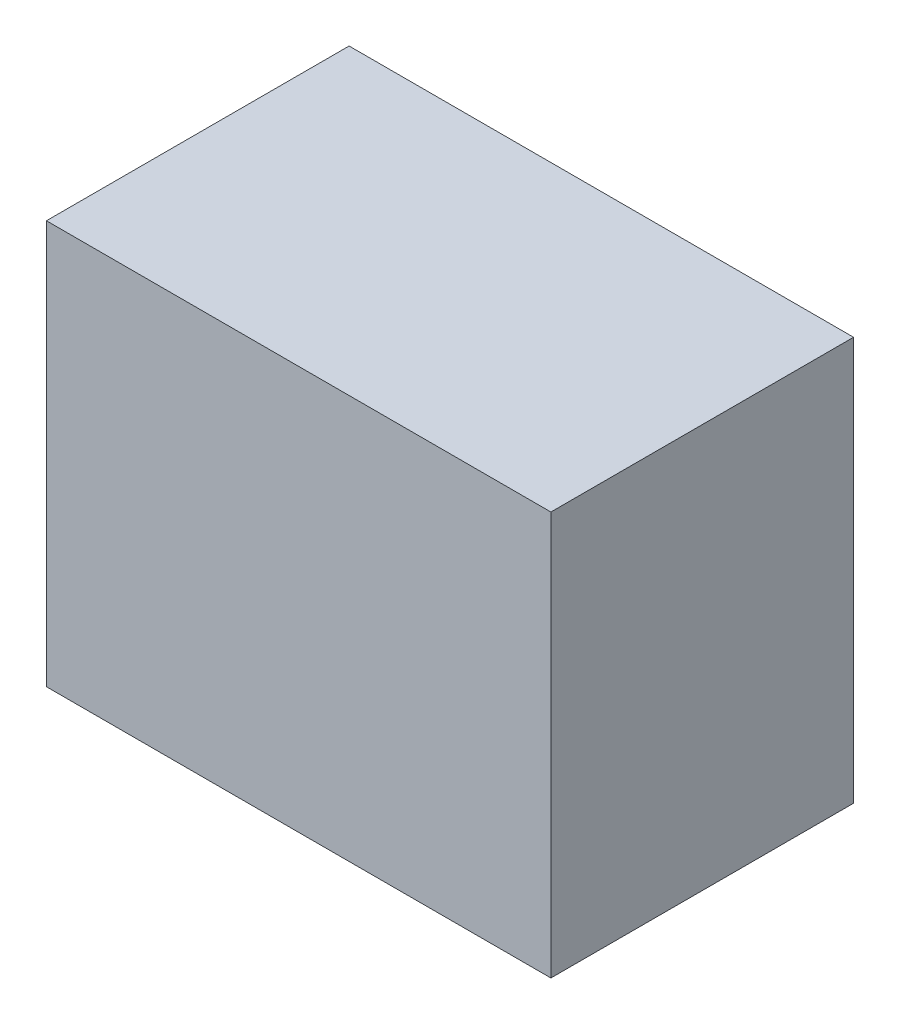
SolidWorks part; units mm, degrees
ref_plane "Front Plane" through (0, 0, 0) normal (0, 0, 1) x (1, 0, 0)
ref_plane "Top Plane" through (0, 0, 0) normal (0, 1, 0) x (1, 0, 0)
ref_plane "Right Plane" through (0, 0, 0) normal (1, 0, 0) x (0, 0, -1)
sketch "Sketch1" plane through (0, 0, 0) normal (0, 0, 1) x (1, 0, 0)
  line L1 (-4.3797, 3.0263) -> (45.6203, 3.0263)
  line L2 (-4.3797, 3.0263) -> (-4.3797, -36.9737)
  line L3 (-4.3797, -36.9737) -> (45.6203, -36.9737)
  line L4 (45.6203, 3.0263) -> (45.6203, -36.9737)
  dimension "D1" = 50
  dimension "D2" = 40
extrude "Boss-Extrude1" add sketch "Sketch1" along normal blind 30
